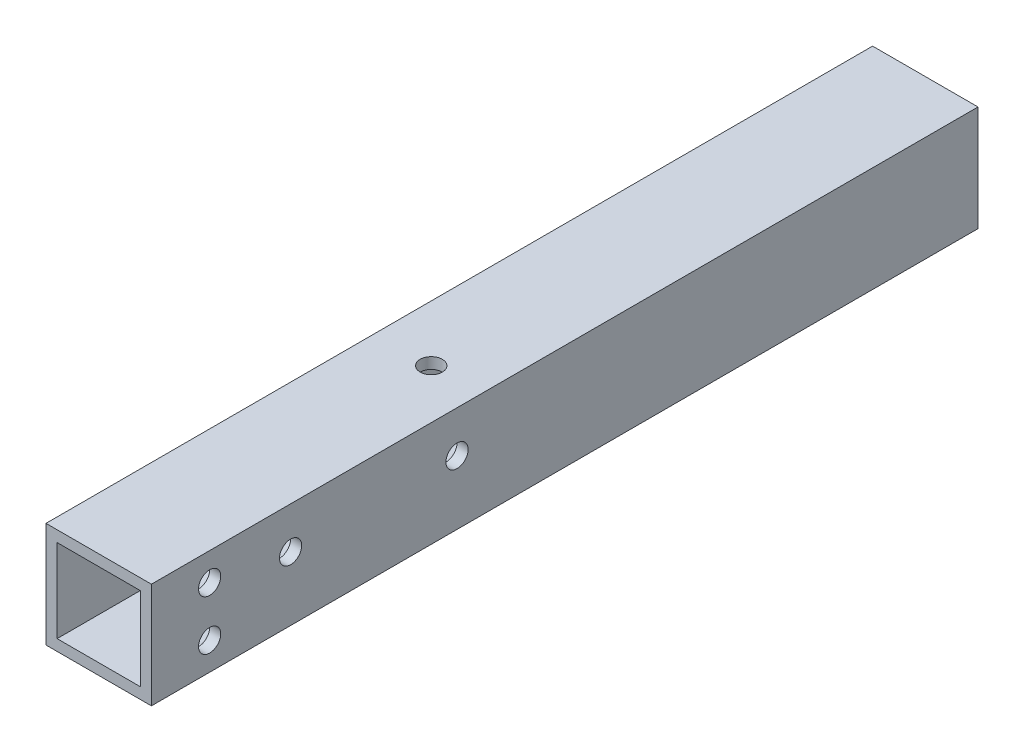
SolidWorks part; units mm, degrees
material "1060 Alloy"
ref_plane "Front Plane" through (0, 0, 0) normal (0, 0, 1) x (1, 0, 0)
ref_plane "Top Plane" through (0, 0, 0) normal (0, 1, 0) x (1, 0, 0)
ref_plane "Right Plane" through (0, 0, 0) normal (1, 0, 0) x (0, 0, -1)
sketch "Sketch1" plane through (0, 0, 0) normal (0, 0, 1) x (1, 0, 0)
  line L0 (-7.5, 7.5) -> (7.5, 7.5)
  line L1 (-9.5, -9.5) -> (9.5, -9.5)
  line L2 (-9.5, -9.5) -> (-9.5, 9.5)
  line L3 (-9.5, 9.5) -> (9.5, 9.5)
  line L4 (9.5, -9.5) -> (9.5, 9.5)
  line L5 (-9.5, -9.5) -> (9.5, 9.5) construction
  line L6 (-9.5, 9.5) -> (9.5, -9.5) construction
  line L7 (7.5, -7.5) -> (7.5, 7.5)
  line L8 (-7.5, -7.5) -> (7.5, -7.5)
  line L9 (-7.5, -7.5) -> (-7.5, 7.5)
  point P0 (0, 0)
  dimension "D1" = 19
  dimension "D2" = 19
  dimension "D3" = 2
extrude "Boss-Extrude1" add sketch "Sketch1" along normal blind 149
sketch "Sketch2" plane through (9.5, 0, 0) normal (1, 0, 0) x (0, 0, -1)
  circle A0 centre (-138.5, 4.5) radius 2
  circle A1 centre (-138.5, -4.5) radius 2
extrude "Cut-Extrude1" cut sketch "Sketch2" against normal blind 10
sketch "Sketch5" plane through (0, 9.5, 0) normal (0, 1, 0) x (1, 0, 0)
  line L0 (9.5, -149) -> (-9.5, -149) construction
  line L1 (9.5, -149) -> (9.5, 0) construction
  circle A0 centre (0.61, -89.67) radius 2
  dimension "D2" = 4
  dimension "D1" = 59.33
  dimension "D3" = 8.89
extrude "Cut-Extrude2" cut sketch "Sketch5" against normal through all
sketch "Sketch6" plane through (-9.5, 0, 0) normal (-1, 0, 0) x (0, 0, 1)
  line L2 (149, 9.5) -> (149, -9.5) construction
  line L3 (149, 9.5) -> (0, 9.5) construction
  circle A0 centre (93.91, 2) radius 2
  circle A1 centre (123.91, 2) radius 2
  dimension "D5" = 4
  dimension "D6" = 4
  dimension "D1" = 30
  dimension "D2" = 25.09
  dimension "D3" = 7.5
  dimension "D4" = 7.5
extrude "Cut-Extrude3" cut sketch "Sketch6" against normal through all
